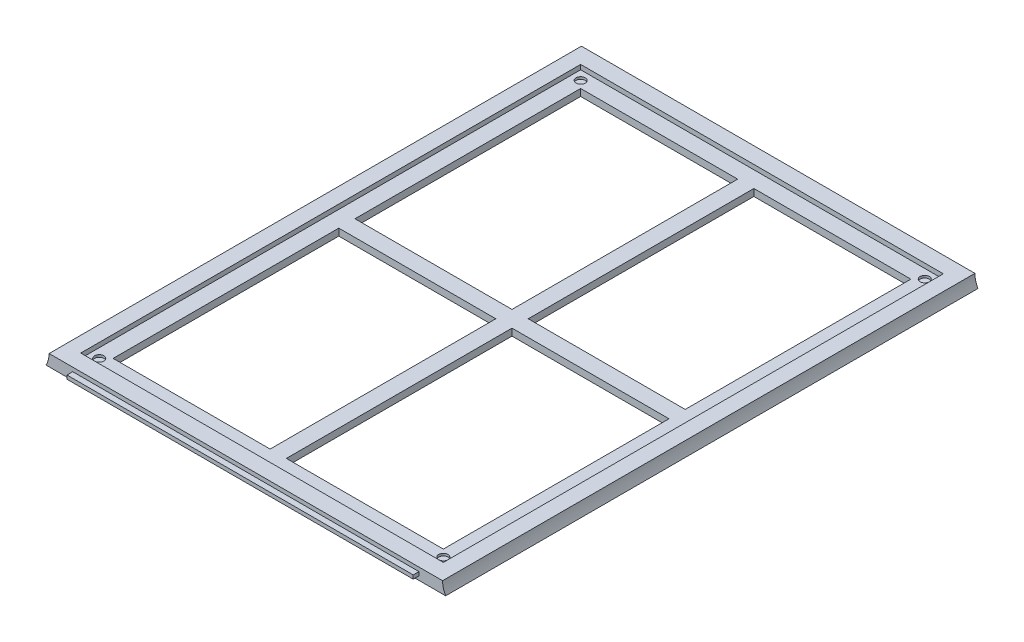
SolidWorks part; units mm, degrees
ref_plane "Plano frontal" through (0, 0, 0) normal (0, 0, 1) x (1, 0, 0)
ref_plane "Plano superior" through (0, 0, 0) normal (0, 1, 0) x (1, 0, 0)
ref_plane "Plano direito" through (0, 0, 0) normal (1, 0, 0) x (0, 0, -1)
sketch "Esboço2" plane through (0, 0, 0) normal (0, 0, 1) x (1, 0, 0)
  line L0 (-158.0256, 4.746) -> (11.9744, 4.746)
  line L1 (13.3142, -0.254) -> (-159.3653, -0.254)
  line L2 (-148.0256, 3.246) -> (1.9744, 3.246)
  line L3 (-148.0256, 3.246) -> (-148.0256, 1.246)
  line L4 (-148.0256, 1.246) -> (1.9744, 1.246)
  line L5 (1.9744, 3.246) -> (1.9744, 1.246)
  arc A0 (11.9744, 4.746) -> (13.3142, -0.254) centre (21.9744, 4.746) ccw
  arc A1 (-158.0256, 4.746) -> (-159.3653, -0.254) centre (-168.0256, 4.746) cw
extrude "Ressalto-extrusão1" add sketch "Esboço2" along normal blind 230
sketch "Esboço3" plane through (0, 4.746, 0) normal (0, -1, 0) x (1, 0, 0)
  line L0 (-73.0256, 230) -> (-73.0256, 0) construction
  line L1 (-159.3653, 230) -> (13.3142, 230) construction
  line L2 (-159.3653, 0) -> (13.3142, 0) construction
  line L4 (-151.3656, 223) -> (5.3144, 223)
  line L5 (-151.3656, 223) -> (-151.3656, 7)
  line L6 (-151.3656, 7) -> (5.3144, 7)
  line L7 (5.3144, 223) -> (5.3144, 7)
  line L8 (-151.3656, 223) -> (5.3144, 7) construction
  line L9 (-151.3656, 7) -> (5.3144, 223) construction
  point P6 (-73.0256, 115)
  dimension "D1" = 156.68
  dimension "D2" = 216
sketch "Esboço4" plane through (0, 0, 230) normal (0, 0, 1) x (1, 0, 0)
  line L0 (1.9744, 3.246) -> (-148.0256, 3.246) construction
  line L1 (-147.8256, 3.046) -> (1.7744, 3.046)
  line L2 (-147.8256, 3.046) -> (-147.8256, 1.446)
  line L3 (-147.8256, 1.446) -> (1.7744, 1.446)
  line L4 (1.7744, 3.046) -> (1.7744, 1.446)
  line L5 (-148.0256, 1.246) -> (1.9744, 1.246) construction
  line L6 (-148.0256, 3.246) -> (-148.0256, 1.246) construction
  line L7 (1.9744, 1.246) -> (1.9744, 3.246) construction
  dimension "D1" = 0.2
  dimension "D2" = 0.2
  dimension "D3" = 0.2
  dimension "D4" = 0.2
extrude "Ressalto-extrusão2" add sketch "Esboço4" along normal blind 2.48 separate body
sketch "Esboço6" plane through (0, 0, 0) normal (0, 0, -1) x (-1, 0, 0)
  line L1 (-1.9744, 3.246) -> (148.0256, 3.246)
  line L2 (-1.9744, 3.246) -> (-1.9744, 1.246)
  line L3 (-1.9744, 1.246) -> (148.0256, 1.246)
  line L4 (148.0256, 3.246) -> (148.0256, 1.246)
extrude "Ressalto-extrusão4" add sketch "Esboço6" against normal blind 230
sketch "Esboço7" plane through (0, 4.746, 0) normal (0, -1, 0) x (1, 0, 0)
  line L0 (-151.3656, 223) -> (5.3144, 7) construction
  line L2 (-144.3656, 213.3498) -> (-144.3656, 14)
  line L3 (-144.3656, 14) -> (-1.6856, 14)
  line L4 (-1.6856, 213.6065) -> (-1.6856, 14)
  line L5 (-151.3656, 223) -> (-151.3656, 7) construction
  line L6 (5.3144, 223) -> (5.3144, 7) construction
  line L7 (-144.3656, 215.9998) -> (-1.6856, 215.9998)
  line L8 (-151.3656, 7) -> (5.3144, 7) construction
  line L11 (-144.3656, 213.3498) -> (-144.3656, 215.9998)
  line L12 (-1.6856, 215.9998) -> (-1.6856, 213.6065)
  line L13 (-151.3656, 223) -> (5.3144, 223) construction
  line L15 (-69.5256, 216) -> (-76.5256, 216)
  line L16 (-69.5256, 216) -> (-69.5256, 14)
  line L17 (-69.5256, 14) -> (-76.5256, 14)
  line L18 (-76.5256, 216) -> (-76.5256, 14)
  line L19 (-69.5256, 216) -> (-76.5256, 14) construction
  line L20 (-69.5256, 14) -> (-76.5256, 216) construction
  line L21 (-1.6856, 118.5) -> (-144.3656, 118.5)
  line L22 (-1.6856, 118.5) -> (-1.6856, 111.5)
  line L23 (-1.6856, 111.5) -> (-144.3656, 111.5)
  line L24 (-144.3656, 118.5) -> (-144.3656, 111.5)
  line L25 (-1.6856, 118.5) -> (-144.3656, 111.5) construction
  line L26 (-1.6856, 111.5) -> (-144.3656, 118.5) construction
  point P0 (-73.0256, 115)
  point P8 (-73.0256, 115)
  point P19 (-73.0256, 115)
  point P24 (-73.0256, 115)
  dimension "D1" = 7
  dimension "D2" = 7
  dimension "D3" = 7
  dimension "D4" = 7.0002
  dimension "D5" = 7
  dimension "D6" = 7
extrude "Corte-extrusão6" cut sketch "Esboço3" along normal blind 2
sketch "Esboço8" plane through (0, 2.746, 0) normal (0, 1, 0) x (1, 0, 0)
  line L0 (-76.5256, -216) -> (-76.5256, -14) construction
  line L1 (-144.3656, -14) -> (-76.5256, -14)
  line L2 (-144.3656, -14) -> (-144.3656, -111.5)
  line L3 (-144.3656, -111.5) -> (-76.5256, -111.5)
  line L4 (-76.5256, -14) -> (-76.5256, -111.5)
  line L5 (-1.6856, -111.5) -> (-144.3656, -111.5) construction
  line L7 (-69.5256, -14) -> (-1.6856, -14)
  line L8 (-69.5256, -14) -> (-69.5256, -111.5)
  line L9 (-69.5256, -111.5) -> (-1.6856, -111.5)
  line L10 (-1.6856, -14) -> (-1.6856, -111.5)
  line L11 (-144.3656, -118.5) -> (-76.5256, -118.5)
  line L12 (-144.3656, -118.5) -> (-144.3656, -216)
  line L13 (-144.3656, -216) -> (-76.5256, -216)
  line L14 (-76.5256, -118.5) -> (-76.5256, -216)
  line L15 (-1.6856, -118.5) -> (-69.5256, -118.5)
  line L16 (-1.6856, -118.5) -> (-1.6856, -216)
  line L17 (-1.6856, -216) -> (-69.5256, -216)
  line L18 (-69.5256, -118.5) -> (-69.5256, -216)
extrude "Corte-extrusão7" cut sketch "Esboço8" against normal blind 20
sketch "Esboço9" plane through (0, 2.746, 0) normal (0, 1, 0) x (1, 0, 0)
  line L1 (-151.3656, -7) -> (5.3144, -7)
  line L2 (-151.3656, -7) -> (-151.3656, -223)
  line L3 (-151.3656, -223) -> (5.3144, -223)
  line L4 (5.3144, -7) -> (5.3144, -223)
  line L5 (-144.3656, -14) -> (-76.5256, -14)
  line L6 (-144.3656, -14) -> (-144.3656, -111.5)
  line L7 (-144.3656, -111.5) -> (-76.5256, -111.5)
  line L8 (-76.5256, -14) -> (-76.5256, -111.5)
  line L9 (-69.5256, -14) -> (-1.6856, -14)
  line L10 (-69.5256, -14) -> (-69.5256, -111.5)
  line L11 (-69.5256, -111.5) -> (-1.6856, -111.5)
  line L12 (-1.6856, -14) -> (-1.6856, -111.5)
  line L13 (-144.3656, -118.5) -> (-76.5256, -118.5)
  line L14 (-144.3656, -118.5) -> (-144.3656, -216)
  line L15 (-144.3656, -216) -> (-76.5256, -216)
  line L16 (-76.5256, -118.5) -> (-76.5256, -216)
  line L17 (-69.5256, -118.5) -> (-1.6856, -118.5)
  line L18 (-69.5256, -118.5) -> (-69.5256, -216)
  line L19 (-69.5256, -216) -> (-1.6856, -216)
  line L20 (-1.6856, -118.5) -> (-1.6856, -216)
  line L26 (-148.2508, -10.0792) -> (2.1996, -219.9208) construction
  line L27 (-148.2508, -219.9208) -> (2.1996, -10.0792) construction
  point P31 (-73.0256, -115)
  point P815 (-148.2508, -10.0792)
sketch "Esboço14" plane through (0, 2.746, 0) normal (0, 1, 0) x (1, 0, 0)
  circle A0 centre (-147.3656, -11) radius 2
  circle A1 centre (1.3144, -11) radius 2
  circle A2 centre (-147.3656, -219) radius 2
  circle A4 centre (1.3144, -219) radius 2
  point P2 (-73.0256, -115)
extrude "Corte-extrusão9" cut sketch "Esboço14" against normal blind 1
